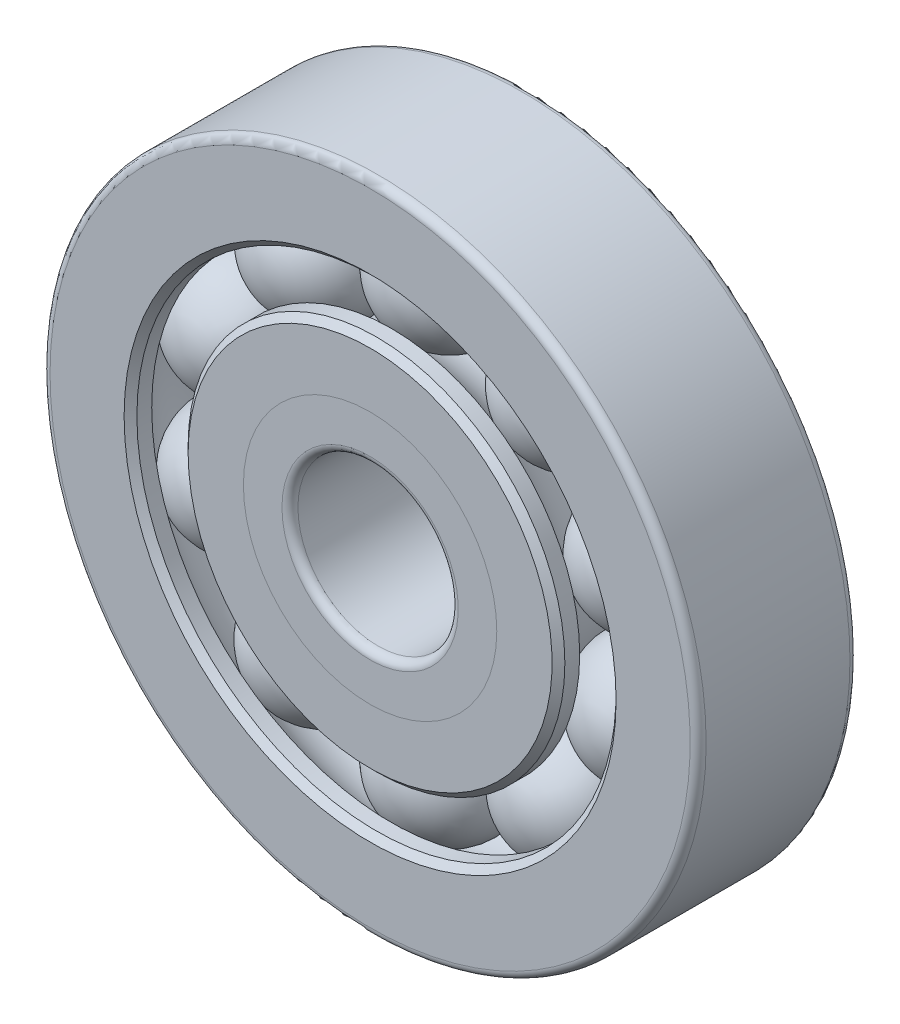
SolidWorks part; units mm, degrees
ref_plane "Front Plane" through (0, 0, 0) normal (0, 0, 1) x (1, 0, 0)
ref_plane "Top Plane" through (0, 0, 0) normal (0, 1, 0) x (1, 0, 0)
ref_plane "Right Plane" through (0, 0, 0) normal (1, 0, 0) x (0, 0, -1)
sketch "Sketch1" plane through (0, 0, 0) normal (1, 0, 0) x (0, 0, -1)
  line L0 (-3.9624, 0) -> (3.9624, 0) construction
  line L9 (0, 16.2687) -> (0, 0) construction
  line L10 (-3.9624, 3.9751) -> (3.9624, 3.9751)
  line L11 (3.9624, 3.9751) -> (3.9624, 9.3421)
  line L12 (3.9624, 9.3421) -> (-3.9624, 9.3421)
  line L13 (-3.9624, 9.3421) -> (-3.9624, 3.9751)
  line L14 (-3.9624, 11.8821) -> (3.9624, 11.8821)
  line L15 (3.9624, 11.8821) -> (3.9624, 16.2687)
  line L16 (3.9624, 16.2687) -> (-3.9624, 16.2687)
  line L17 (-3.9624, 16.2687) -> (-3.9624, 11.8821)
  line L18 (-3.175, 10.6121) -> (3.175, 10.6121) construction
  line L20 (3.9624, 6.2831) -> (-3.9624, 6.2831) construction
  line L21 (0, 7.4371) -> (0, 6.2831)
  line L22 (0, 6.2831) -> (0, 5.1291)
  line L23 (0, 5.1291) -> (0, 3.9751)
  circle A0 centre (0, 10.6121) radius 3.175
  point P17 (0, 13.7871)
  dimension "ID" = 7.9502
  dimension "OD" = 32.5374
  dimension "Ball Diameter" = 6.35
  dimension "Ball Pattern Diameter" = 21.2242
  dimension "D6" = 2.54
  dimension "Width" = 7.9248
sketch "Sketch2" plane through (0, 0, 0) normal (0, 0, 1) x (1, 0, 0)
  circle A0 centre (0, 0) radius 10.6121 construction
  circle A1 centre (0, 10.6121) radius 3.175
  circle A2 centre (6.2376, 8.5854) radius 3.175
  circle A3 centre (10.0927, 3.2793) radius 3.175
  circle A4 centre (10.0927, -3.2793) radius 3.175
  circle A5 centre (6.2376, -8.5854) radius 3.175
  circle A6 centre (0, -10.6121) radius 3.175
  circle A7 centre (-6.2376, -8.5854) radius 3.175
  circle A8 centre (-10.0927, -3.2793) radius 3.175
  circle A9 centre (-10.0927, 3.2793) radius 3.175
  circle A10 centre (-6.2376, 8.5854) radius 3.175
  circle A15 centre (0, 0) radius 3.9751 construction
  circle A16 centre (0, 0) radius 16.2687 construction
  point P36 (0, 0)
  dimension "ID" = 7.9502
  dimension "OD" = 32.5374
  dimension "No. of Balls" = 10
sketch "Sketch3" plane through (0, 0, 0) normal (1, 0, 0) x (0, 0, -1)
  line L1 (3.9624, 3.9751) -> (3.9624, 9.3421) construction
  line L2 (-3.9624, 9.3421) -> (-3.9624, 3.9751) construction
  line L3 (3.9624, 9.3421) -> (-3.9624, 9.3421) construction
  line L5 (3.9624, 3.9751) -> (3.9624, 9.3421)
  line L6 (-3.9624, 9.3421) -> (-3.9624, 3.9751)
  line L7 (3.9624, 9.3421) -> (-3.9624, 9.3421)
  line L8 (-3.9624, 16.2687) -> (-3.9624, 11.8821) construction
  line L9 (3.9624, 16.2687) -> (-3.9624, 16.2687) construction
  line L10 (3.9624, 11.8821) -> (3.9624, 16.2687) construction
  line L11 (-3.9624, 11.8821) -> (3.9624, 11.8821) construction
  line L12 (-3.9624, 16.2687) -> (-3.9624, 11.8821)
  line L13 (3.9624, 16.2687) -> (-3.9624, 16.2687)
  line L14 (3.9624, 11.8821) -> (3.9624, 16.2687)
  line L15 (-3.9624, 11.8821) -> (3.9624, 11.8821)
  line L16 (-3.9624, 3.9751) -> (3.9624, 3.9751) construction
  line L17 (-3.9624, 3.9751) -> (3.9624, 3.9751)
revolve "Revolve2" add sketch "Sketch3" angle 360 about L0
sketch "Sketch4" plane through (0, 0, 0) normal (1, 0, 0) x (0, 0, -1)
  circle A0 centre (0, 10.6121) radius 3.175 construction
  circle A1 centre (0, 10.6121) radius 3.175
revolve "Cut-Revolve1" cut sketch "Sketch4" angle 360 about L0
sketch "Sketch5" plane through (0, 0, 0) normal (1, 0, 0) x (0, 0, -1)
  line L0 (-3.175, 10.6121) -> (3.175, 10.6121) construction
  line L1 (-3.175, 10.6121) -> (3.175, 10.6121)
  circle A0 centre (0, 10.6121) radius 3.175 construction
  arc A1 (3.175, 10.6121) -> (-3.175, 10.6121) centre (0, 10.6121) ccw
revolve "Revolve3" add sketch "Sketch5" angle 360 about L18
pattern_circular "CirPattern1" count 10 over 360 about axis through (0, 0, 0) along (0, 0, 1) of bodies 109
fillet "Fillet1" radius 0.3962 2 edges at (16.2687, 0, 3.9624) (16.2687, 0, -3.9624)
fillet "Fillet2" radius 0.3962 2 edges at (3.9751, 0, -3.9624) (3.9751, 0, 3.9624)
chamfer "Chamfer1" distance 0.317 angle 45 2 edges at (11.8821, 0, -3.9624) (11.8821, 0, 3.9624)
chamfer "Chamfer2" distance 0.317 angle 45 2 edges at (9.3421, 0, 3.9624) (9.3421, 0, -3.9624)
sketch "Split Line" plane through (0, 0, 0) normal (0, 0, 1) x (1, 0, 0)
  circle A0 centre (0, 0) radius 6.2831
split "Split1" trim tools "Split Line" bodies to split 108 resulting bodies 128 129
equation "\"D1@CirPattern1\"=\"No. of Balls@Sketch2\""
equation "\"D6@Sketch1\"=\"Ball Diameter@Sketch1\"*0.4"
equation "\"D1@Fillet1\"=\"Width@Sketch1\"/20"
equation "\"D1@Fillet2\"=\"Width@Sketch1\"/20"
equation "\"D1@Chamfer1\"=\"Width@Sketch1\"/25"
equation "\"D1@Chamfer2\"=\"Width@Sketch1\"/25"
equation "\"ID@Sketch2\"=\"ID@Sketch1\""
equation "\"OD@Sketch2\" = \"OD@Sketch1\""
